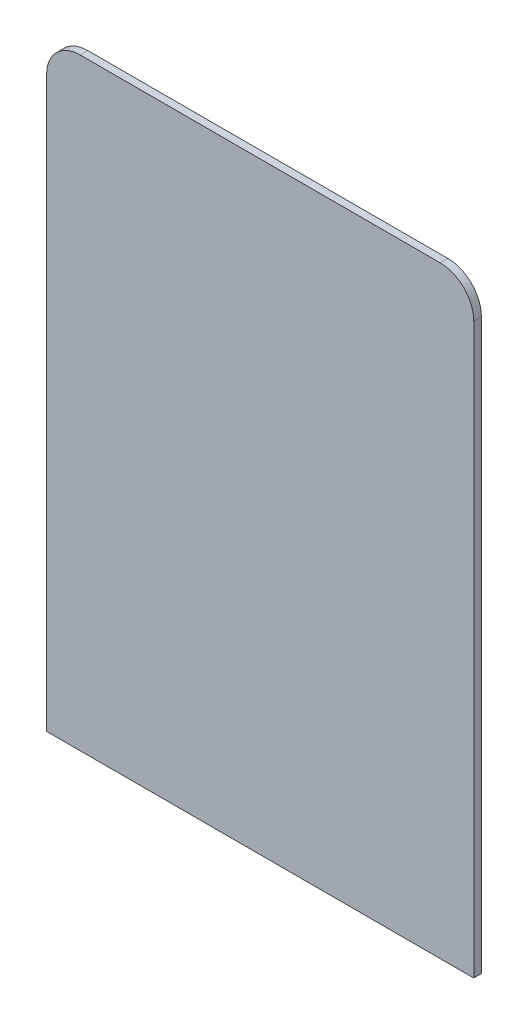
SolidWorks part; units mm, degrees
material "Alloy Steel"
ref_plane "Front Plane" through (0, 0, 0) normal (0, 0, 1) x (1, 0, 0)
ref_plane "Top Plane" through (0, 0, 0) normal (0, 1, 0) x (1, 0, 0)
ref_plane "Right Plane" through (0, 0, 0) normal (1, 0, 0) x (0, 0, -1)
sketch "Sketch1"
sketch "Sketch2" plane through (0, 0, 0) normal (0, 0, 1) x (1, 0, 0)
  line L0 (0, 254) -> (0, 0) construction
  line L1 (-92.075, 0) -> (92.075, 0)
  line L2 (-92.075, 0) -> (-92.075, 236.855)
  line L4 (92.075, 0) -> (92.075, 236.855)
  line L5 (-74.93, 254) -> (74.93, 254)
  arc A0 (74.93, 254) -> (92.075, 236.855) centre (74.93, 236.855) cw
  arc A1 (-74.93, 254) -> (-92.075, 236.855) centre (-74.93, 236.855) ccw
  point P4 (0, 0)
  point P14 (92.075, 251.3834)
  dimension "D3" = 17.145
  dimension "D1" = 184.15
  dimension "D4" = 254
extrude "Boss-Extrude1" add sketch "Sketch2" along normal blind 3.175
sketch "Sketch4" plane through (0, 0, 3.175) normal (0, 0, 1) x (1, 0, 0)
  line L0 (-92.075, 236.855) -> (-92.075, 0) construction
  line L1 (74.93, 254) -> (-74.93, 254) construction
  line L2 (92.075, 0) -> (92.075, 236.855) construction
  line L3 (-92.075, 236.855) -> (-92.075, 0)
  line L4 (74.93, 254) -> (-74.93, 254)
  line L5 (92.075, 0) -> (92.075, 236.855)
  line L6 (88.9, 0) -> (88.9, 236.855)
  line L7 (74.93, 250.825) -> (-74.93, 250.825)
  line L8 (-88.9, 236.855) -> (-88.9, 0)
  arc A0 (-74.93, 254) -> (-92.075, 236.855) centre (-74.93, 236.855) ccw construction
  arc A1 (92.075, 236.855) -> (74.93, 254) centre (74.93, 236.855) ccw construction
  arc A2 (-74.93, 254) -> (-92.075, 236.855) centre (-74.93, 236.855) ccw
  arc A3 (92.075, 236.855) -> (74.93, 254) centre (74.93, 236.855) ccw
  arc A4 (88.9, 236.855) -> (74.93, 250.825) centre (74.93, 236.855) ccw
  arc A5 (-74.93, 250.825) -> (-88.9, 236.855) centre (-74.93, 236.855) ccw
  line M9 (-92.075, 236.855) -> (-92.075, 0)
  line M10 (-92.075, 0) -> (92.075, 0)
  line M11 (92.075, 0) -> (92.075, 236.855)
  arc M12 (92.075, 236.855) -> (74.93, 254) centre (74.93, 236.855) ccw
  line M13 (74.93, 254) -> (-74.93, 254)
  arc M14 (-74.93, 254) -> (-92.075, 236.855) centre (-74.93, 236.855) ccw
  dimension "D1" = 3.175
extrude "Thickness Reduction for sides" cut sketch "Sketch4" against normal through all contours A5 L7 A4 L6 L8 M10 M11 M12 M13 M14 M9
